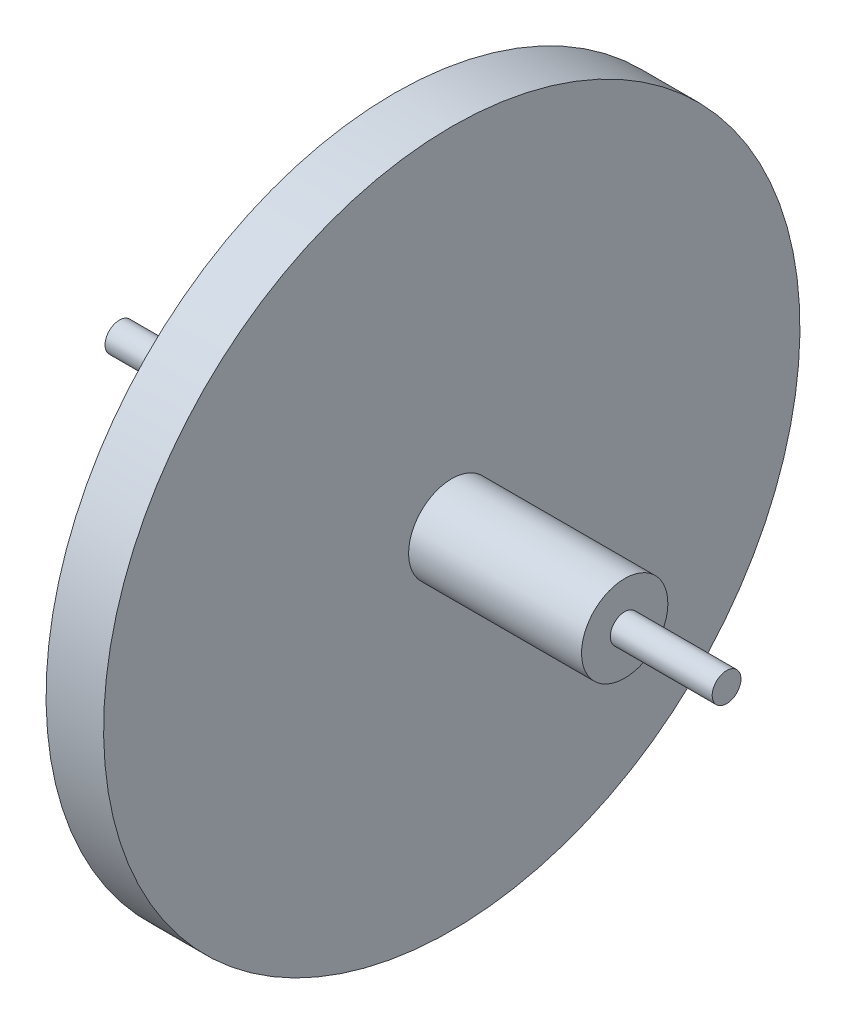
SolidWorks part; units mm, degrees
ref_plane "Front Plane" through (0, 0, 0) normal (0, 0, 1) x (1, 0, 0)
ref_plane "Top Plane" through (0, 0, 0) normal (0, 1, 0) x (1, 0, 0)
ref_plane "Right Plane" through (0, 0, 0) normal (1, 0, 0) x (0, 0, -1)
sketch "Sketch1" plane through (0, 0, 0) normal (0, 0, 1) x (1, 0, 0)
  line L0 (-105.5, 5) -> (-64.9073, 5)
  line L1 (-64.9073, 5) -> (-64.9073, 10)
  line L2 (-64.9073, 10) -> (-10, 10)
  line L3 (-10, 10) -> (-10, 121)
  line L4 (-10, 121) -> (10, 121)
  line L5 (10, 121) -> (10, 15)
  line L6 (10, 15) -> (70.0927, 15)
  line L7 (70.0927, 15) -> (70.0927, 5)
  line L8 (70.0927, 5) -> (105.5, 5)
  line L9 (105.5, 5) -> (105.5, 0)
  line L10 (116.05, 0) -> (-116.05, 0) construction
  line L11 (105.5, 0) -> (-105.5, 0)
  line L12 (-105.5, 0) -> (-105.5, 5)
  point P2 (0, 0)
  point P16 (0, 121)
  dimension "D1" = 211
  dimension "D2" = 135
  dimension "D3" = 121
  dimension "D4" = 20
  dimension "D5" = 5
  dimension "D6" = 5
  dimension "D7" = 10
revolve "Revolve1" add sketch "Sketch1" angle 360 about L11
